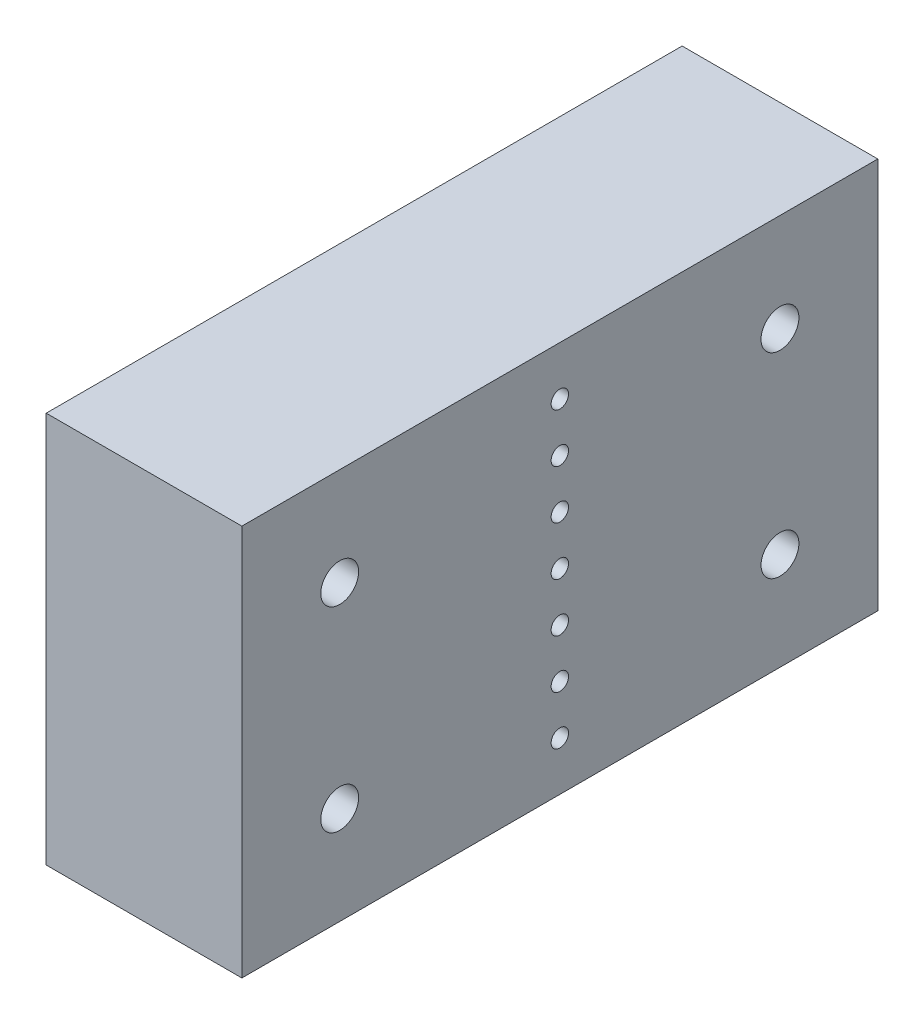
SolidWorks part; units mm, degrees
ref_plane "Front Plane" through (0, 0, 0) normal (0, 0, 1) x (1, 0, 0)
ref_plane "Top Plane" through (0, 0, 0) normal (0, 1, 0) x (1, 0, 0)
ref_plane "Right Plane" through (0, 0, 0) normal (1, 0, 0) x (0, 0, -1)
sketch "Sketch1" plane through (0, 0, 0) normal (1, 0, 0) x (0, 0, -1)
  line L1 (41.275, -25.4) -> (-41.275, -25.4)
  line L2 (41.275, -25.4) -> (41.275, 25.4)
  line L3 (41.275, 25.4) -> (-41.275, 25.4)
  line L4 (-41.275, -25.4) -> (-41.275, 25.4)
  line L5 (41.275, -25.4) -> (-41.275, 25.4) construction
  line L6 (41.275, 25.4) -> (-41.275, -25.4) construction
  point P0 (0, 0)
  dimension "D1" = 82.55
  dimension "D2" = 50.8
extrude "Boss-Extrude1" add sketch "Sketch1" along normal mid plane 25.4
hole_wizard "#10 (0.1935) Diameter Hole1" positions "Sketch3" profile "Sketch2" hole size "#10" standard "ANSI Inch" end condition through all
sketch "Sketch3" plane through (12.7, 0, 0) normal (1, 0, 0) x (0, 0, -1)
  line L0 (28.575, 12.7) -> (-28.575, 12.7) construction
  line L1 (28.575, 12.7) -> (28.575, -12.7) construction
  line L2 (41.275, -25.4) -> (41.275, 25.4) construction
  line L3 (41.275, 25.4) -> (-41.275, 25.4) construction
  point P0 (28.575, 12.7)
  point P10 (-28.575, 12.7)
  point P11 (-28.575, -12.7)
  point P12 (28.575, -12.7)
  dimension "D3" = 57.15
  dimension "D4" = 25.4
  dimension "D5" = 12.7
  dimension "D6" = 12.7
  dimension "D1" = 2
  dimension "D2" = 2
sketch "Sketch2" plane through (12.7, 12.7, -28.575) normal (0, 1, 0) x (0, 0, -1)
  line L0 (0, 0) -> (0, 25.4)
  line L1 (0, 25.4) -> (2.4574, 25.4)
  line L2 (2.4574, 25.4) -> (2.4574, 0)
  line L5 (2.4574, 0) -> (0, 0)
  line L11 (0, -6.35) -> (0, 107.95) construction
  dimension "Thru Hole Dia." = 4.9149
  dimension "Thru Hole Depth" = 25.4
hole_wizard "#4-40 Tapped Hole1" positions "Sketch5" profile "Sketch4" tap size "#4-40" standard "ANSI Inch" end condition through all
sketch "Sketch5" plane through (12.7, 0, 0) normal (1, 0, 0) x (0, 0, -1)
  line L0 (0, 19.05) -> (0, -19.05) construction
  point P0 (0, 19.05)
  point P12 (0, 0)
  point P21 (0, 12.7)
  point P22 (0, 6.35)
  point P23 (0, 0)
  point P24 (0, -6.35)
  point P25 (0, -12.7)
  point P26 (0, -19.05)
  dimension "D2" = 38.1
  dimension "D1" = 7
sketch "Sketch4" plane through (12.7, 19.05, 0) normal (0, 1, 0) x (0, 0, -1)
  line L0 (0, 0) -> (0, 25.4)
  line L1 (0, 25.4) -> (1.1303, 25.4)
  line L2 (1.1303, 25.4) -> (1.1303, 0)
  line L5 (1.1303, 0) -> (0, 0)
  line L11 (0, -6.35) -> (0, 107.95) construction
  dimension "Thread Major Dia." = 2.2606
  dimension "Thru Tap Drill Depth" = 25.4
